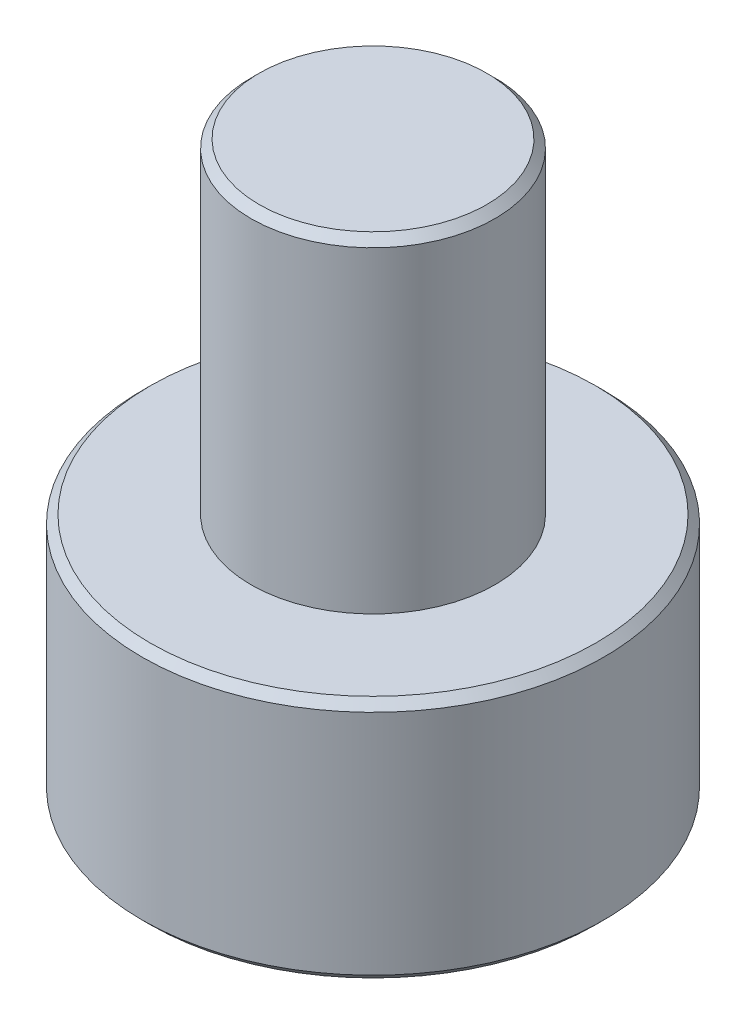
SolidWorks part; units mm, degrees
material "Q235"
ref_plane "前视基准面" through (0, 0, 0) normal (0, 0, 1) x (1, 0, 0)
ref_plane "上视基准面" through (0, 0, 0) normal (0, 1, 0) x (1, 0, 0)
ref_plane "右视基准面" through (0, 0, 0) normal (1, 0, 0) x (0, 0, -1)
sketch "草图1" plane through (0, 0, 0) normal (0, 1, 0) x (1, 0, 0)
  circle A0 centre (0, 0) radius 2.84
  dimension "D1" = 5.68
extrude "杯头部分" add sketch "草图1" along normal blind 3
sketch "草图2" plane through (0, 3, 0) normal (0, 1, 0) x (1, 0, 0)
  circle A0 centre (0, 0) radius 1.5
  dimension "D1" = 3
extrude "螺柱部分" add sketch "草图2" along normal blind 4
cosmetic thread "装饰螺纹线1" parameters "D2"=2.459
sketch "草图3" plane through (0, 0, 0) normal (0, -1, 0) x (1, 0, 0)
  line L1 (1.29, -0.7448) -> (1.29, 0.7448)
  line L2 (1.29, 0.7448) -> (0, 1.4896)
  line L3 (0, 1.4896) -> (-1.29, 0.7448)
  line L4 (-1.29, 0.7448) -> (-1.29, -0.7448)
  line L5 (-1.29, -0.7448) -> (0, -1.4896)
  line L6 (0, -1.4896) -> (1.29, -0.7448)
  circle A0 centre (0, 0) radius 1.29 construction
  dimension "D1" = 2.58
extrude "沉头内六角" cut sketch "草图3" against normal blind 1.3
chamfer "修饰性倒角" distance 0.1 angle 45 3 edges at (0, 7, 1.5) (0, 3, 2.84) (0, 0, 2.84)
